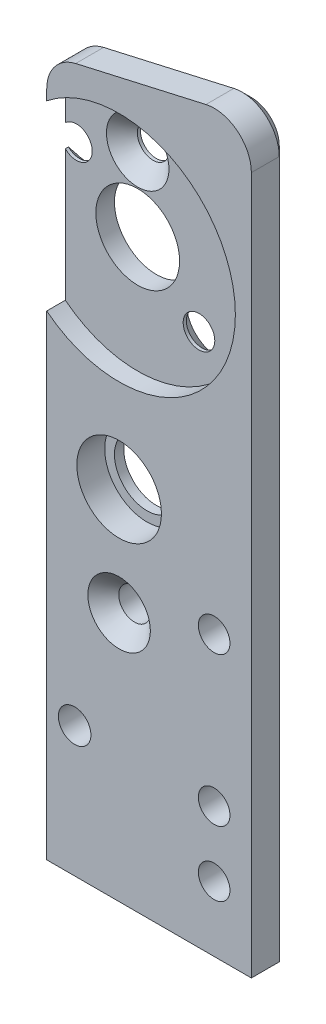
SolidWorks part; units mm, degrees
ref_plane "Plano frontal" through (0, 0, 0) normal (0, 0, 1) x (1, 0, 0)
ref_plane "Plano superior" through (0, 0, 0) normal (0, 1, 0) x (1, 0, 0)
ref_plane "Plano direito" through (0, 0, 0) normal (1, 0, 0) x (0, 0, -1)
sketch "Esboço1" plane through (0, 0, 0) normal (0, 0, 1) x (1, 0, 0)
  line L0 (0, 0) -> (22, 0)
  line L1 (22, 0) -> (22, 80)
  line L2 (22, 80) -> (0, 75)
  line L3 (0, 75) -> (0, 0)
  dimension "D1" = 22
  dimension "D2" = 80
  dimension "D3" = 75
extrude "Ressalto-extrusão1" add sketch "Esboço1" along normal blind 4
fillet "Filete1" radius 4 2 edges at (22, 80, 2) (0, 75, 2)
chamfer "Chanfro1" distance 1 angle 45 5 edges at (0, 35.9035, 0) (0.8738, 74.3025, 0) (10.1135, 77.2985, 0) (20.4954, 78.1151, 0) (22, 37.4945, 0)
sketch "Esboço2" plane through (0, 0, 4) normal (0, 0, 1) x (1, 0, 0)
  line L0 (0, 71.8071) -> (0, 0) construction
  point P0 (14.1, 34.4)
  dimension "D1" = 34.4
  dimension "D2" = 14.1
sketch "Esboço4" plane through (0, 0, 0) normal (0, 0, -1) x (-1, 0, 0)
  line L0 (0, 0) -> (-7.7809, 0) construction
  line L1 (-1, 0) -> (-21, 0) construction
  line L2 (-7.7809, 0) -> (-7.7809, 38.3937) construction
  line L3 (0, 0) -> (10, 0) construction
  line L4 (10, 0) -> (10, 13) construction
  line L5 (10, 13) -> (-21, 13) construction
  line L6 (10, 13) -> (-7.7809, 38.3937) construction
  circle A0 centre (10, 13) radius 31 construction
  dimension "D3" = 62
  dimension "D1" = 10
  dimension "D2" = 13
  dimension "D4" = 55
hole_wizard "Furo de diâmetro Ø7.0 (7)1" positions "3DSketch1" profile "Esboço5" hole size "Ø7.0" standard "ISO" end condition through all
sketch3d "3DSketch1"
  point P0 (7.7809, 38.3937, 0)
sketch "Esboço5" plane through (7.7809, 38.3937, 0) normal (1, 0, 0) x (0, 1, 0)
  line L0 (0, 0) -> (0, 4)
  line L1 (0, 4) -> (3.5, 4)
  line L2 (3.5, 4) -> (3.5, 0)
  line L5 (3.5, 0) -> (0, 0)
  line L11 (0, -6.35) -> (0, 107.95) construction
  dimension "Thru Hole Dia." = 7
  dimension "Thru Hole Depth" = 4
sketch "Esboço7" plane through (0, 0, 0) normal (0, 0, -1) x (-1, 0, 0)
  line L0 (-18, 7) -> (-18, 14) construction
  line L1 (-1, 0) -> (-21, 0) construction
  line L2 (-18, 14) -> (-3, 14) construction
  line L3 (0, 71.8071) -> (0, 0) construction
  point P0 (-18, 7)
  dimension "D1" = 18
  dimension "D2" = 7
  dimension "D3" = 7
  dimension "D4" = 3
hole_wizard "Escareado para parafuso com cabeça escareada elevada de M31" positions "3DSketch3" profile "Esboço8" countersink size "M3" standard "ISO" end condition through all
sketch3d "3DSketch3"
  point P0 (18, 7, 0)
  point P3 (18, 14, 0)
sketch "Esboço8" plane through (18, 7, 0) normal (1, 0, 0) x (0, 1, 0)
  line L0 (0, 0) -> (0, 4)
  line L1 (0, 4) -> (1.7, 4)
  line L2 (1.7, 4) -> (1.7, 1.45)
  line L3 (1.7, 1.45) -> (3.15, 0)
  line L5 (3.15, 0) -> (0, 0)
  line L6 (-1.7, 1.45) -> (-3.15, 0) construction
  line L11 (0, -6.35) -> (0, 107.95) construction
  dimension "Thru Hole Dia." = 3.4
  dimension "Thru Hole Depth" = 4
  dimension "Near C'Sink Dia." = 6.3
  dimension "Near C'Sink Angle" = 90
sketch "Esboço9" plane through (0, 0, 0) normal (0, -1, 0) x (1, 0, 0)
  line L0 (0, 4) -> (0, 0) construction
  line L1 (0, 2) -> (22, 2) construction
  line L2 (22, 4) -> (22, 1) construction
  point P8 (4, 2)
  point P9 (8, 2)
  point P10 (12, 2)
  dimension "D1" = 4
  dimension "D2" = 4
  dimension "D3" = 4
hole_wizard "Broca de rosquear para tarraxa de M21" positions "3DSketch4" profile "Esboço11" hole size "M2" standard "ISO"
sketch3d "3DSketch4"
  point P0 (4, 0, 2)
  point P6 (12, 0, 2)
sketch "Esboço11" plane through (4, 0, 2) normal (1, 0, 0) x (0, 0, -1)
  line L0 (0, 0) -> (0, 8.4807)
  line L1 (0, 8.4807) -> (0.8, 8)
  line L2 (0.8, 8) -> (0.8, 0)
  line L5 (0.8, 0) -> (0, 0)
  line L10 (0, 8.4807) -> (-0.8, 8) construction
  line L11 (0, -6.35) -> (0, 107.95) construction
  dimension "Hole Dia." = 1.6
  dimension "Hole Depth" = 8
  dimension "Drill Angle" = 118
sketch "Esboço12" plane through (0, 0, 4) normal (0, 0, 1) x (1, 0, 0)
  circle A0 centre (7.7809, 38.3937) radius 3.5 construction
  circle A1 centre (7.7809, 38.3937) radius 4.55
  point P0 (7.7809, 38.3937)
  dimension "D1" = 9.1
sketch "Esboço15" plane through (0, 0, 0) normal (0, 0, -1) x (-1, 0, 0)
  line L0 (-7.7809, 38.3937) -> (-7.7809, 49.8937) construction
  line L1 (-7.7809, 49.8937) -> (-7.7809, 60.8937) construction
  line L4 (-14.3689, 55.3657) -> (-1.1929, 66.4217) construction
  line L6 (0, 71.8071) -> (0, 0) construction
  circle A0 centre (-7.7809, 49.8937) radius 11.5 construction
  circle A1 centre (-7.7809, 60.8937) radius 8.6 construction
  circle A2 centre (-7.7809, 49.8937) radius 4.6
  point P4 (-7.7809, 49.8937)
  dimension "D2" = 17.2
  dimension "D6" = 9.2
  dimension "D1" = 11.5
  dimension "D3" = 50
  dimension "D4" = 180
  dimension "D5" = 0
  dimension "D7" = 11
hole_wizard "Furo de diâmetro Ø9.0 (9)3" positions "3DSketch9" profile "Esboço22" hole size "Ø9.0" standard "ISO" end condition through all
sketch3d "3DSketch9"
  point P12 (7.7809, 60.8937, 0)
sketch "Esboço22" plane through (7.7809, 60.8937, 0) normal (1, 0, 0) x (0, 1, 0)
  line L0 (0, 0) -> (0, 4)
  line L1 (0, 4) -> (4.5, 4)
  line L2 (4.5, 4) -> (4.5, 0)
  line L5 (4.5, 0) -> (0, 0)
  line L11 (0, -6.35) -> (0, 107.95) construction
  dimension "Thru Hole Dia." = 9
  dimension "Thru Hole Depth" = 4
sketch "Esboço24" plane through (0, 0, 4) normal (0, 0, 1) x (1, 0, 0)
  circle A0 centre (7.7809, 49.8937) radius 4.6
  circle A1 centre (7.7809, 49.8937) radius 4.6 construction
  point P0 (7.7809, 49.8937)
hole_wizard "Escareado para parafuso Allen sextavado escareado de M31" positions "3DSketch14" profile "Esboço28" countersink size "M3" standard "ISO" end condition through all
sketch3d "3DSketch14"
  point P0 (14.3689, 55.3657, 0)
  point P3 (1.1929, 66.4217, 0)
sketch "Esboço28" plane through (14.3689, 55.3657, 0) normal (1, 0, 0) x (0, 1, 0)
  line L0 (0, 0) -> (0, 4)
  line L1 (0, 4) -> (1.7, 4)
  line L2 (1.7, 4) -> (1.7, 1.66)
  line L3 (1.7, 1.66) -> (3.36, 0)
  line L5 (3.36, 0) -> (0, 0)
  line L6 (-1.7, 1.66) -> (-3.36, 0) construction
  line L11 (0, -6.35) -> (0, 107.95) construction
  dimension "Thru Hole Dia." = 3.4
  dimension "Thru Hole Depth" = 4
  dimension "Near C'Sink Dia." = 6.72
  dimension "Near C'Sink Angle" = 90
sketch "Esboço30" plane through (0, 0, 0) normal (0, 0, -1) x (-1, 0, 0)
  line L0 (-22, 0) -> (-22, 74.9889) construction
  line L1 (0, 0) -> (-22, 0) construction
  point P0 (-18, 30)
  dimension "D1" = 4
  dimension "D2" = 30
hole_wizard "Escareado para parafuso com cabeça escareada chata de M31" positions "3DSketch16" profile "Esboço31" countersink size "M3" standard "ISO"
sketch3d "3DSketch16"
  point P0 (18, 30, 0)
sketch "Esboço31" plane through (18, 30, 0) normal (1, 0, 0) x (0, 1, 0)
  line L0 (0, 0) -> (0, 5.0215)
  line L1 (0, 5.0215) -> (1.7, 4)
  line L2 (1.7, 4) -> (1.7, 1.45)
  line L3 (1.7, 1.45) -> (3.15, 0)
  line L5 (3.15, 0) -> (0, 0)
  line L6 (-1.7, 1.45) -> (-3.15, 0) construction
  line L10 (0, 5.0215) -> (-1.7, 4) construction
  line L11 (0, -6.35) -> (0, 107.95) construction
  dimension "Hole Dia." = 3.4
  dimension "Hole Depth" = 4
  dimension "Near C'Sink Dia." = 6.3
  dimension "Near C'Sink Angle" = 90
  dimension "Drill Angle" = 118
extrude "Corte-extrusão1" cut sketch "Esboço12" against normal blind 3
sketch "Esboço32" plane through (0, 0, 4) normal (0, 0, 1) x (1, 0, 0)
  line L0 (7.7809, 68.8937) -> (7.7809, 49.8937) construction
  line L1 (0, 71.8071) -> (0, 67.6329) construction
  line L2 (7.7809, 68.8937) -> (7.7809, 26.8937) construction
  dimension "D1" = 19
  dimension "D2" = 42
hole_wizard "Furo de diâmetro Ø3.5 (3.5)1" positions "3DSketch19" profile "Esboço35" hole size "Ø3.5" standard "ISO" end condition through all
sketch3d "3DSketch19"
  point P0 (3, 14, 0)
sketch "Esboço35" plane through (3, 14, 0) normal (1, 0, 0) x (0, 1, 0)
  line L0 (0, 0) -> (0, 4)
  line L1 (0, 4) -> (1.75, 4)
  line L2 (1.75, 4) -> (1.75, 0)
  line L5 (1.75, 0) -> (0, 0)
  line L11 (0, -6.35) -> (0, 107.95) construction
  dimension "Thru Hole Dia." = 3.5
  dimension "Thru Hole Depth" = 4
sketch "Esboço36" plane through (0, 0, 4) normal (0, 0, 1) x (1, 0, 0)
  circle A0 centre (7.7809, 60.8937) radius 12.5
  dimension "D1" = 25
extrude "Corte-extrusão4" cut sketch "Esboço36" against normal blind 2
sketch "Esboço37" plane through (0, 0, 0) normal (0, 0, -1) x (-1, 0, 0)
  line L0 (-7.7809, 38.3937) -> (-7.7809, 26.8937) construction
  line L1 (-7.7809, 38.3937) -> (-7.7809, 68.8937) construction
  dimension "D1" = 30.5
  dimension "D2" = 11.5
sketch "Esboço39" plane through (0, 0, 2) normal (0, 0, 1) x (1, 0, 0)
  point P0 (7.7809, 68.8937)
  point P1 (0, 0)
sketch "Esboço40" plane through (0, 0, 4) normal (0, 0, 1) x (1, 0, 0)
  point P0 (7.7809, 26.8937)
  point P1 (0, 0)
hole_wizard "Escareado para parafuso Allen sextavado escareado de M32" positions "3DSketch21" profile "Esboço41" countersink size "M3" standard "ISO" end condition through all
sketch3d "3DSketch21"
  point P4 (7.7809, 26.8937, 4)
  point P7 (7.7809, 68.8937, 2)
sketch "Esboço41" plane through (7.7809, 26.8937, 4) normal (1, 0, 0) x (0, -1, 0)
  line L0 (0, 0) -> (0, 4.2548)
  line L1 (0, 4.2548) -> (1.7, 4.2548)
  line L2 (1.7, 4.2548) -> (1.7, 1.66)
  line L3 (1.7, 1.66) -> (3.36, 0)
  line L5 (3.36, 0) -> (0, 0)
  line L6 (-1.7, 1.66) -> (-3.36, 0) construction
  line L11 (0, -6.35) -> (0, 107.95) construction
  dimension "Thru Hole Dia." = 3.4
  dimension "Thru Hole Depth" = 4.2548
  dimension "Near C'Sink Dia." = 6.72
  dimension "Near C'Sink Angle" = 90
